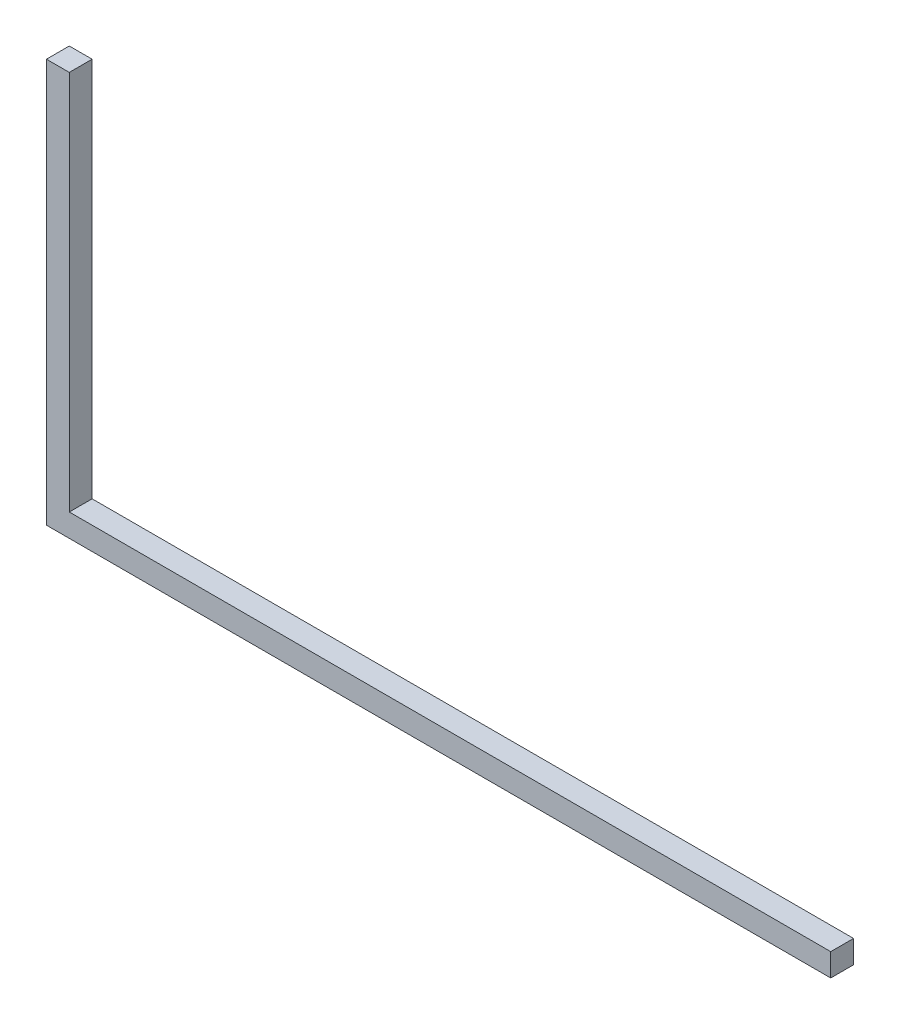
SolidWorks part; units mm, degrees
ref_plane "前视基准面" through (0, 0, 0) normal (0, 0, 1) x (1, 0, 0)
ref_plane "上视基准面" through (0, 0, 0) normal (0, 1, 0) x (1, 0, 0)
ref_plane "右视基准面" through (0, 0, 0) normal (1, 0, 0) x (0, 0, -1)
sketch "草图1" plane through (0, 0, 0) normal (0, 0, 1) x (1, 0, 0)
  line L0 (0, 0) -> (0, 250)
  line L1 (0, 250) -> (-15, 250)
  line L2 (-15, 250) -> (-15, -15)
  line L3 (-15, -15) -> (500, -15)
  line L4 (500, -15) -> (500, 0)
  line L5 (500, 0) -> (0, 0)
  dimension "D1" = 15
  dimension "D2" = 15
  dimension "D3" = 500
  dimension "D4" = 250
extrude "凸台-拉伸1" add sketch "草图1" along normal blind 15
